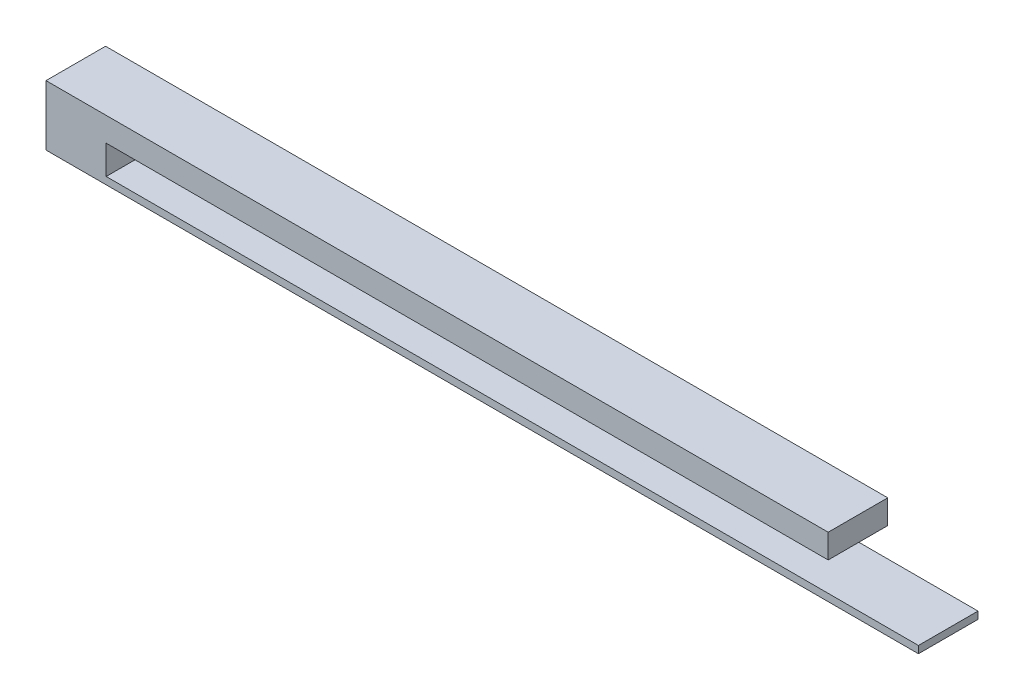
SolidWorks part; units mm, degrees
ref_plane "Front Plane" through (0, 0, 0) normal (0, 0, 1) x (1, 0, 0)
ref_plane "Top Plane" through (0, 0, 0) normal (0, 1, 0) x (1, 0, 0)
ref_plane "Right Plane" through (0, 0, 0) normal (1, 0, 0) x (0, 0, -1)
sketch "Sketch1" plane through (0, 0, 0) normal (0, 1, 0) x (1, 0, 0)
  line L1 (-72.5, 4.95) -> (72.5, 4.95)
  line L2 (-72.5, 4.95) -> (-72.5, -4.95)
  line L3 (-72.5, -4.95) -> (72.5, -4.95)
  line L4 (72.5, 4.95) -> (72.5, -4.95)
  line L5 (-72.5, 4.95) -> (72.5, -4.95) construction
  line L6 (-72.5, -4.95) -> (72.5, 4.95) construction
  point P0 (0, 0)
  dimension "D1" = 145
  dimension "D2" = 9.9
extrude "Boss-Extrude1" add sketch "Sketch1" along normal blind 10
sketch "Sketch2" plane through (72.5, 0, 0) normal (1, 0, 0) x (0, 0, -1)
  line L0 (-4.95, 10) -> (4.95, 10) construction
  line L1 (-7.588, 6) -> (7.588, 6)
  line L2 (-7.588, 6) -> (-7.588, 1.2)
  line L3 (-7.588, 1.2) -> (7.588, 1.2)
  line L4 (7.588, 6) -> (7.588, 1.2)
  line L5 (-7.588, 6) -> (7.588, 1.2) construction
  line L6 (-7.588, 1.2) -> (7.588, 6) construction
  line L7 (-4.95, 0) -> (4.95, 0) construction
  point P0 (0, 3.6)
  dimension "D1" = 4
  dimension "D2" = 1.2
extrude "Cut-Extrude1" cut sketch "Sketch2" against normal offset from surface (135 mm away) 10 up to face at (-72.5, 5, 0)
sketch "Sketch3" plane through (72.5, 0, 0) normal (1, 0, 0) x (0, 0, -1)
  line L1 (-5.6586, 10.7996) -> (5.6586, 10.7996)
  line L2 (-5.6586, 10.7996) -> (-5.6586, 5)
  line L3 (-5.6586, 5) -> (5.6586, 5)
  line L4 (5.6586, 10.7996) -> (5.6586, 5)
  line L5 (-5.6586, 10.7996) -> (5.6586, 5) construction
  line L6 (-5.6586, 5) -> (5.6586, 10.7996) construction
  point P0 (0, 7.8998)
extrude "Cut-Extrude2" cut sketch "Sketch3" against normal blind 15
